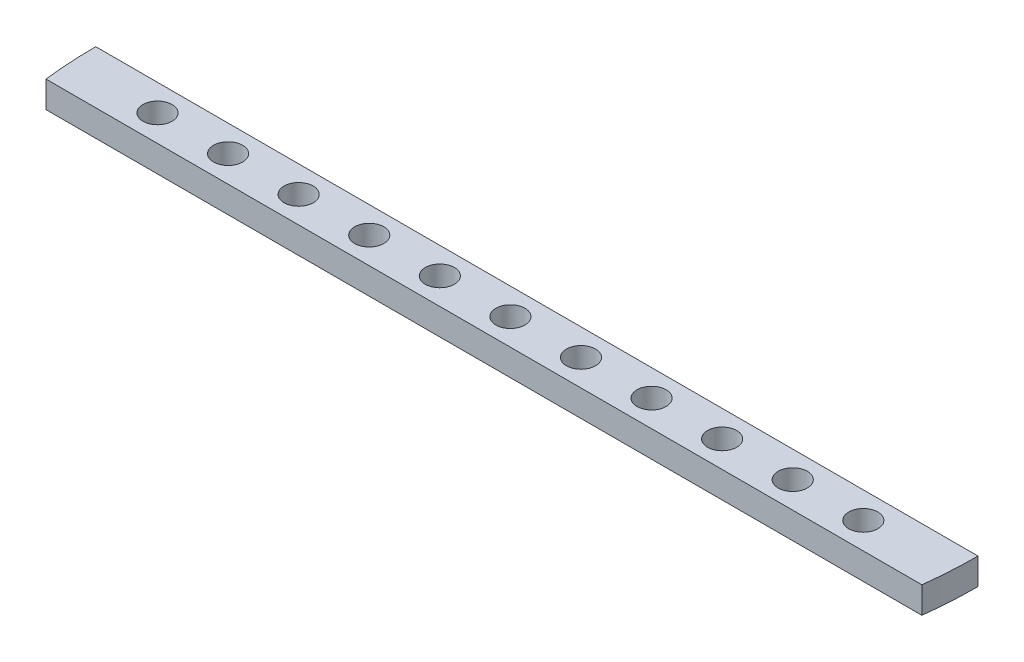
SolidWorks part; units mm, degrees
ref_plane "前视基准面" through (0, 0, 0) normal (0, 0, 1) x (1, 0, 0)
ref_plane "上视基准面" through (0, 0, 0) normal (0, 1, 0) x (1, 0, 0)
ref_plane "右视基准面" through (0, 0, 0) normal (1, 0, 0) x (0, 0, -1)
sketch "草图1" plane through (0, 0, 0) normal (0, 1, 0) x (1, 0, 0)
  line L0 (-50, 0) -> (50, 0)
  arc A0 (50, 0) -> (-50, 0) centre (0, 0) cw
extrude "凸台-拉伸1" add sketch "草图1" along normal blind 4
sketch "草图2" plane through (0, 4, 0) normal (0, 1, 0) x (1, 0, 0)
  line L2 (0, -10.623) -> (10, -10.623)
  line L3 (10, -10.623) -> (10, -30.623)
  line L4 (10, -30.623) -> (-30, -30.623)
  line L5 (-30, -30.623) -> (-30, -10.623)
  line L6 (-30, -10.623) -> (0, -10.623)
extrude "切除-拉伸1" cut sketch "草图2" against normal blind 10
sketch "草图3" plane through (0, 4, 0) normal (0, 1, 0) x (1, 0, 0)
  circle A0 centre (-34.75, -15.623) radius 2.25
  circle A1 centre (-34.75, -25.623) radius 2.25
  circle A2 centre (14.75, -25.623) radius 2.25
  circle A3 centre (14.75, -15.623) radius 2.25
extrude "切除-拉伸2" cut sketch "草图3" against normal blind 10
sketch "草图4" plane through (0, 4, 0) normal (0, 1, 0) x (1, 0, 0)
  circle A0 centre (0, -3) radius 1.65
  circle A1 centre (8, -3) radius 1.65
  circle A2 centre (16, -3) radius 1.65
  circle A3 centre (24, -3) radius 1.65
  circle A4 centre (32, -3) radius 1.65
  circle A5 centre (40, -3) radius 1.65
  circle A6 centre (-40, -3) radius 1.65
  circle A7 centre (-32, -3) radius 1.65
  circle A8 centre (-24, -3) radius 1.65
  circle A9 centre (-16, -3) radius 1.65
  circle A10 centre (-8, -3) radius 1.65
extrude "切除-拉伸3" cut sketch "草图4" against normal blind 10
sketch "草图5" plane through (0, 4, 0) normal (0, 1, 0) x (1, 0, 0)
  line L0 (0, 0) -> (0, -8)
  line L1 (0, -8) -> (-49.3559, -8)
  line L2 (-49.3559, -8) -> (49.3559, -8)
  arc A0 (-50, 0) -> (50, 0) centre (0, 0) ccw construction
  circle M13 centre (14.75, -15.623) radius 2.25
  circle M14 centre (14.75, -25.623) radius 2.25
  circle M15 centre (-34.75, -25.623) radius 2.25
  circle M16 centre (-34.75, -15.623) radius 2.25
  line M17 (-30, -30.623) -> (-30, -10.623)
  line M18 (-30, -10.623) -> (10, -10.623)
  line M19 (10, -10.623) -> (10, -30.623)
  line M20 (10, -30.623) -> (-30, -30.623)
  arc M21 (-50, 0) -> (50, 0) centre (0, 0) ccw
extrude "切除-拉伸4" cut sketch "草图5" against normal blind 10 contours L2 L1 M21 M14 M16 M20 M17 M18 M19 M15 M13
sketch "草图7" plane through (0, 0, 0) normal (0, 0, -1) x (-1, 0, 0)
  line L0 (-50, 4) -> (-50, 3)
  line L1 (-50, 4) -> (-50, 0) construction
  line L2 (-50, 3) -> (50, 3)
  line L3 (50, 4) -> (50, 0) construction
  line L5 (50, 4) -> (49.3559, 4) construction
  line L6 (49.6779, 4) -> (-50, 4)
  line L7 (50, 3) -> (50, 4)
  line L8 (50, 4) -> (49.6779, 4)
extrude "切除-拉伸6" cut sketch "草图7" against normal blind 10
sketch "草图8" plane through (0, 3, 0) normal (0, 1, 0) x (1, 0, 0)
  line L0 (0, -3) -> (0, -6)
  line L2 (0, -6) -> (53.5987, -6)
  line L3 (53.5987, -6) -> (-59.9071, -6)
  line L4 (-59.9071, -6) -> (0, -44.0854)
  line L5 (0, -44.0854) -> (53.5987, -6)
  line M7 (-49.3559, -8) -> (49.3559, -8)
  arc M8 (49.3559, -8) -> (50, 0) centre (0, 0) ccw
  arc M10 (-50, 0) -> (-49.3559, -8) centre (0, 0) ccw
extrude "切除-拉伸7" cut sketch "草图8" against normal blind 10 contours L2 L3 M10 M7 M8
